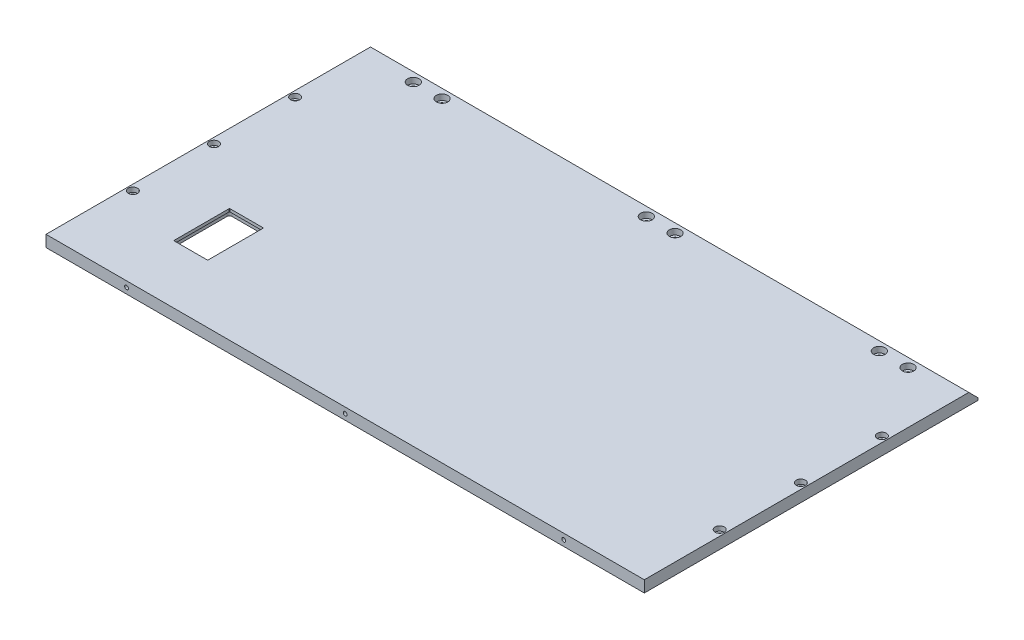
SolidWorks part; units mm, degrees
material "Bakelite Black"
ref_plane "Front" through (0, 0, 0) normal (0, 0, 1) x (1, 0, 0)
ref_plane "Top" through (0, 0, 0) normal (0, 1, 0) x (1, 0, 0)
ref_plane "Right" through (0, 0, 0) normal (1, 0, 0) x (0, 0, -1)
sketch "Sketch1" plane through (0, 0, 0) normal (0, 1, 0) x (1, 0, 0)
  line L1 (-260, 290) -> (260, 290)
  line L2 (-260, 290) -> (-260, 0)
  line L3 (-260, 0) -> (260, 0)
  line L4 (260, 290) -> (260, 0)
  line L5 (-260, 290) -> (260, 0) construction
  line L6 (-260, 0) -> (260, 290) construction
  point P0 (0, 145)
  dimension "D1" = 520
  dimension "D2" = 290
extrude "Boss-Extrude1" add sketch "Sketch1" along normal blind 10
hole_wizard "CBORE for M5 SHCS1" positions "Sketch3" profile "Sketch4" counterbore size "M5" standard "ANSI Metric"
sketch "Sketch3" plane through (0, 10, 0) normal (0, 1, 0) x (1, 0, 0)
  line L0 (0, -50) -> (0, 50) construction
  line L1 (260, 290) -> (-260, 290) construction
  point P0 (-215, 274.25)
  point P2 (-190, 274.25)
  point P4 (-12.5, 274.25)
  point P6 (12.5, 274.25)
  point P8 (190, 274.25)
  point P10 (215, 274.25)
  dimension "D1" = 12.5
  dimension "D2" = 12.5
  dimension "D3" = 25
  dimension "D4" = 25
  dimension "D5" = 190
  dimension "D6" = 190
  dimension "D7" = 15.75
sketch "Sketch4" plane through (-215, 10, -274.25) normal (1, 0, 0) x (0, 0, 1)
  line L0 (0, 0) -> (0, 13.1524)
  line L1 (0, 13.1524) -> (2.75, 11.5)
  line L2 (2.75, 11.5) -> (2.75, 5)
  line L3 (2.75, 5) -> (5, 5)
  line L4 (5, 5) -> (5, 0)
  line L5 (5, 0) -> (0, 0)
  line L10 (0, 13.1524) -> (-2.75, 11.5) construction
  line L11 (0, -6.35) -> (0, 107.95) construction
  dimension "Hole Dia." = 5.5
  dimension "Hole Depth" = 11.5
  dimension "C'Bore Dia." = 10
  dimension "C'Bore Depth" = 5
  dimension "Drill Angle" = 118
sketch "Sketch2" plane through (0, 0, 0) normal (1, 0, 0) x (0, 0, -1)
  line L0 (290, 2) -> (290, 10)
  line L1 (290, 10) -> (290, 0) construction
  line L2 (290, 10) -> (282, 10)
  line L3 (290, 10) -> (0, 10) construction
  line L4 (282, 10) -> (290, 2)
  dimension "D1" = 8
  dimension "D2" = 8
extrude "Cut-Extrude1" cut sketch "Sketch2" against normal through all both and the other way through all
hole_wizard "CBORE for M4 SHCS1" positions "Sketch5" profile "Sketch6" counterbore size "M4" standard "ANSI Metric" end condition through all
sketch "Sketch5" plane through (0, 10, 0) normal (0, 1, 0) x (1, 0, 0)
  line L0 (-260, 0) -> (260, 0) construction
  line L1 (260, 0) -> (260, 282) construction
  point P0 (255, 211.5)
  point P2 (255, 141)
  point P4 (255, 70.5)
  dimension "D1" = 70.5
  dimension "D2" = 70.5
  dimension "D3" = 70.5
  dimension "D4" = 5
sketch "Sketch6" plane through (255, 10, -211.5) normal (1, 0, 0) x (0, 0, 1)
  line L0 (0, 0) -> (0, 10)
  line L1 (0, 10) -> (2.25, 10)
  line L3 (2.25, 10) -> (2.25, 4)
  line L4 (2.25, 4) -> (4, 4)
  line L5 (4, 4) -> (4, 0)
  line L7 (4, 0) -> (0, 0)
  line L11 (0, -6.35) -> (0, 107.95) construction
  dimension "Thru Hole Dia." = 4.5
  dimension "Thru Hole Depth" = 10
  dimension "C'Bore Dia." = 8
  dimension "C'Bore Depth" = 4
mirror "Mirror1" about plane through (0, 0, 0) normal (1, 0, 0) of "CBORE for M4 SHCS1"
hole_wizard "M4x0.7 Tapped Hole1" positions "Sketch7" profile "Sketch8" tap size "M4x0.7" standard "ANSI Metric"
sketch "Sketch7" plane through (0, 0, 0) normal (0, 0, 1) x (1, 0, 0)
  line L0 (0, -50) -> (0, 50) construction
  line L1 (-260, 10) -> (260, 10) construction
  point P0 (-190, 5)
  point P2 (0, 5)
  point P4 (190, 5)
  dimension "D1" = 190
  dimension "D2" = 190
  dimension "D3" = 5
sketch "Sketch8" plane through (-190, 5, 0) normal (1, 0, 0) x (0, -1, 0)
  line L0 (0, 0) -> (0, 12.9914)
  line L1 (0, 12.9914) -> (1.65, 12)
  line L2 (1.65, 12) -> (1.65, 0)
  line L5 (1.65, 0) -> (0, 0)
  line L10 (0, 12.9914) -> (-1.65, 12) construction
  line L11 (0, -6.35) -> (0, 107.95) construction
  dimension "Tap Drill Dia." = 3.3
  dimension "Tap Drill Depth" = 12
  dimension "Drill Angle" = 118
cosmetic thread "Hole Thread1" parameters "D1"=8, "D2"=4
cosmetic thread "Hole Thread2" parameters "D1"=8, "D2"=4
cosmetic thread "Hole Thread3" parameters "D1"=8, "D2"=4
sketch "Sketch9" plane through (0, 10, 0) normal (0, 1, 0) x (1, 0, 0)
  line L0 (-260, 282) -> (-260, 0) construction
  line L1 (-199.75, 99.25) -> (-170.25, 99.25)
  line L2 (-199.75, 99.25) -> (-199.75, 50.75)
  line L3 (-199.75, 50.75) -> (-170.25, 50.75)
  line L4 (-170.25, 99.25) -> (-170.25, 50.75)
  line L5 (-199.75, 99.25) -> (-170.25, 50.75) construction
  line L6 (-199.75, 50.75) -> (-170.25, 99.25) construction
  line L7 (-260, 0) -> (260, 0) construction
  point P0 (-185, 75)
  dimension "D1" = 29.5
  dimension "D2" = 48.5
  dimension "D3" = 75
  dimension "D4" = 75
extrude "Cut-Extrude2" cut sketch "Sketch9" against normal through all
fillet "Fillet1" radius 0.5 4 edges at (-170.25, 5, -50.75) (-199.75, 5, -50.75) (-199.75, 5, -99.25) (-170.25, 5, -99.25)
sketch "Sketch10" plane through (0, 0, 0) normal (0, -1, 0) x (1, 0, 0)
  line L0 (-170.75, -99.25) -> (-199.25, -99.25) construction
  line L1 (-165.25, -104.25) -> (-204.75, -104.25)
  line L2 (-165.25, -104.25) -> (-165.25, -45.75)
  line L3 (-165.25, -45.75) -> (-204.75, -45.75)
  line L4 (-204.75, -104.25) -> (-204.75, -45.75)
  line L5 (-199.25, -50.75) -> (-170.75, -50.75) construction
  line L6 (-170.25, -51.25) -> (-170.25, -98.75) construction
  line L7 (-199.75, -98.75) -> (-199.75, -51.25) construction
  dimension "D1" = 5
  dimension "D2" = 5
  dimension "D3" = 5
  dimension "D4" = 5
extrude "Cut-Extrude3" cut sketch "Sketch10" against normal blind 7.5
fillet "Fillet2" radius 2 4 edges at (-204.75, 3.75, -45.75) (-204.75, 3.75, -104.25) (-165.25, 3.75, -104.25) (-165.25, 3.75, -45.75)
hole_wizard "M4x0.7 Tapped Hole2" positions "Sketch11" profile "Sketch12" tap size "M4x0.7" standard "ANSI Metric"
sketch "Sketch11" plane through (0, 0, 0) normal (0, -1, 0) x (-1, 0, 0)
  line L0 (-38.5336, 0) -> (38.5336, 0) construction
  line L1 (260, 290) -> (260, 0) construction
  point P0 (99.4, 175)
  point P2 (210, 175)
  point P4 (210, 140)
  point P6 (99.4, 140)
  dimension "D1" = 140
  dimension "D2" = 35
  dimension "D3" = 110.6
  dimension "D4" = 50
sketch "Sketch12" plane through (-99.4, 0, -175) normal (1, 0, 0) x (0, 0, -1)
  line L0 (0, 0) -> (0, 8.9914)
  line L1 (0, 8.9914) -> (1.65, 8)
  line L2 (1.65, 8) -> (1.65, 0)
  line L5 (1.65, 0) -> (0, 0)
  line L10 (0, 8.9914) -> (-1.65, 8) construction
  line L11 (0, -6.35) -> (0, 107.95) construction
  dimension "Tap Drill Dia." = 3.3
  dimension "Tap Drill Depth" = 8
  dimension "Drill Angle" = 118
cosmetic thread "Hole Thread4" parameters "D1"=6, "D2"=4
cosmetic thread "Hole Thread5" parameters "D1"=6, "D2"=4
cosmetic thread "Hole Thread6" parameters "D1"=6, "D2"=4
cosmetic thread "Hole Thread7" parameters "D1"=6, "D2"=4
